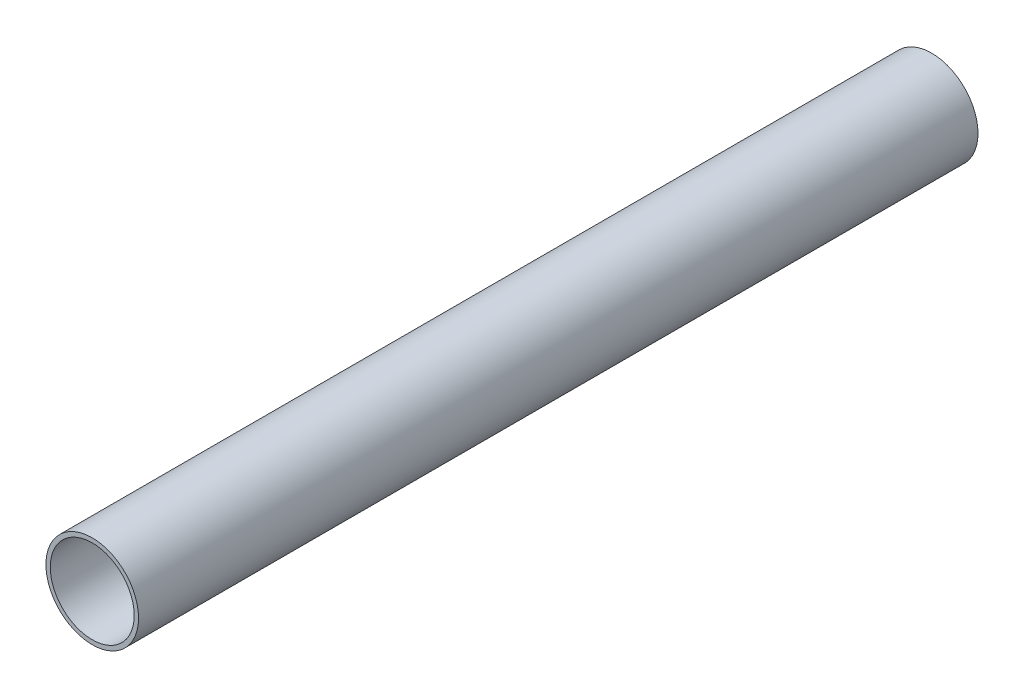
SolidWorks part; units mm, degrees
material "5052 Alloy"
ref_plane "Front Plane" through (0, 0, 0) normal (0, 0, 1) x (1, 0, 0)
ref_plane "Top Plane" through (0, 0, 0) normal (0, 1, 0) x (1, 0, 0)
ref_plane "Right Plane" through (0, 0, 0) normal (1, 0, 0) x (0, 0, -1)
sketch "Sketch1" plane through (0, 0, 0) normal (0, 0, 1) x (1, 0, 0)
  circle A0 centre (0, 0) radius 8
  dimension "D1" = 16
extrude "Extrude1" add sketch "Sketch1" against normal blind 145
sketch "Sketch2" plane through (0, 0, 0) normal (0, 0, 1) x (1, 0, 0)
  circle A0 centre (0, 0) radius 7.25
  dimension "D1" = 14.5
extrude "Cut-Extrude1" cut sketch "Sketch2" against normal through all
